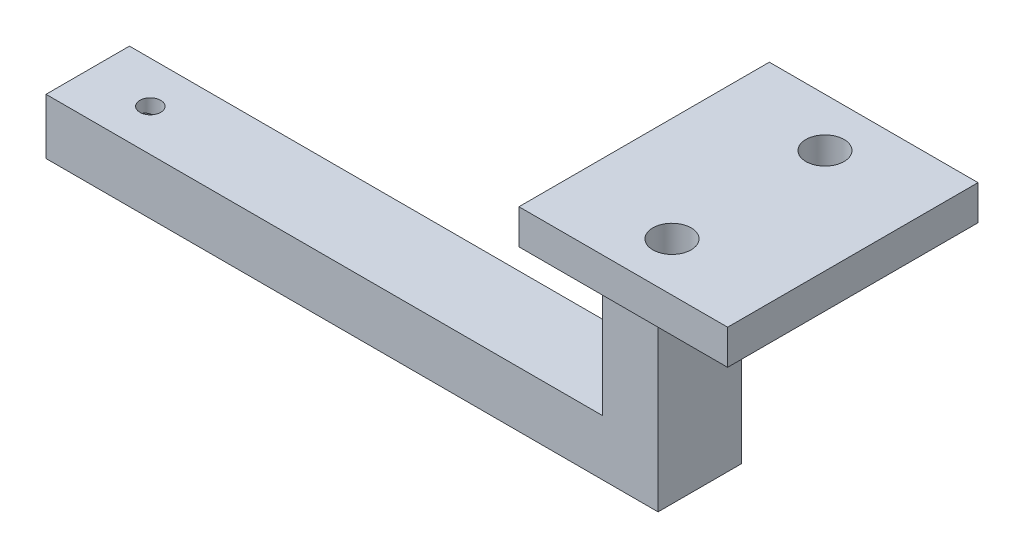
SolidWorks part; units mm, degrees
ref_plane "Front Plane" through (0, 0, 0) normal (0, 0, 1) x (1, 0, 0)
ref_plane "Top Plane" through (0, 0, 0) normal (0, 1, 0) x (1, 0, 0)
ref_plane "Right Plane" through (0, 0, 0) normal (1, 0, 0) x (0, 0, -1)
sketch "Sketch1" plane through (0, 0, 0) normal (0, 0, 1) x (1, 0, 0)
  line L0 (0, 0) -> (0, 40)
  line L1 (0, 40) -> (-8, 40)
  line L2 (-8, 40) -> (-8, 8)
  line L3 (-8, 8) -> (-88, 8)
  line L4 (-88, 8) -> (-88, 0)
  line L5 (-88, 0) -> (0, 0)
  dimension "D1" = 88
  dimension "D2" = 40
  dimension "D3" = 8
  dimension "D4" = 8
extrude "Boss-Extrude1" add sketch "Sketch1" along normal blind 12
sketch "Sketch2" plane through (0, 8, 0) normal (0, 1, 0) x (1, 0, 0)
  line L0 (0, -6) -> (-79, -6) construction
  line L1 (0, -12) -> (0, 0) construction
  circle A0 centre (-79, -6) radius 1.5
  dimension "D2" = 3
  dimension "D1" = 79
extrude "Cut-Extrude1" cut sketch "Sketch2" against normal blind 12
sketch "Sketch3" plane through (-88, 0, 0) normal (-1, 0, 0) x (0, 0, 1)
  line L0 (0, 0) -> (12, 8) construction
  circle A0 centre (6, 4) radius 2.25
  dimension "D1" = 4.5
extrude "Cut-Extrude2" cut sketch "Sketch3" against normal blind 9
sketch "Sketch4" plane through (-8, 0, 0) normal (1, 0, 0) x (0, 0, -1)
  line L0 (-12, 40) -> (0, 40) construction
  line L1 (-24, 40) -> (12, 40)
  line L2 (-24, 40) -> (-24, 35)
  line L3 (-24, 35) -> (12, 35)
  line L4 (12, 40) -> (12, 35)
  line L5 (-12, 0) -> (-12, 40) construction
  line L6 (0, 0) -> (0, 40) construction
  dimension "D1" = 5
  dimension "D2" = 12
  dimension "D3" = 12
extrude "Boss-Extrude2" add sketch "Sketch4" along normal blind 30
sketch "Sketch5" plane through (0, 40, 0) normal (0, 1, 0) x (1, 0, 0)
  line L0 (7, 12) -> (7, -24) construction
  line L1 (22, 12) -> (-8, 12) construction
  line L2 (22, -24) -> (-8, -24) construction
  circle A0 centre (7, -17) radius 2.75
  circle A1 centre (7, 5) radius 2.75
  dimension "D1" = 22
  dimension "D2" = 7
  dimension "D3" = 5.5
  dimension "D4" = 5.5
extrude "Cut-Extrude3" cut sketch "Sketch5" against normal blind 30
